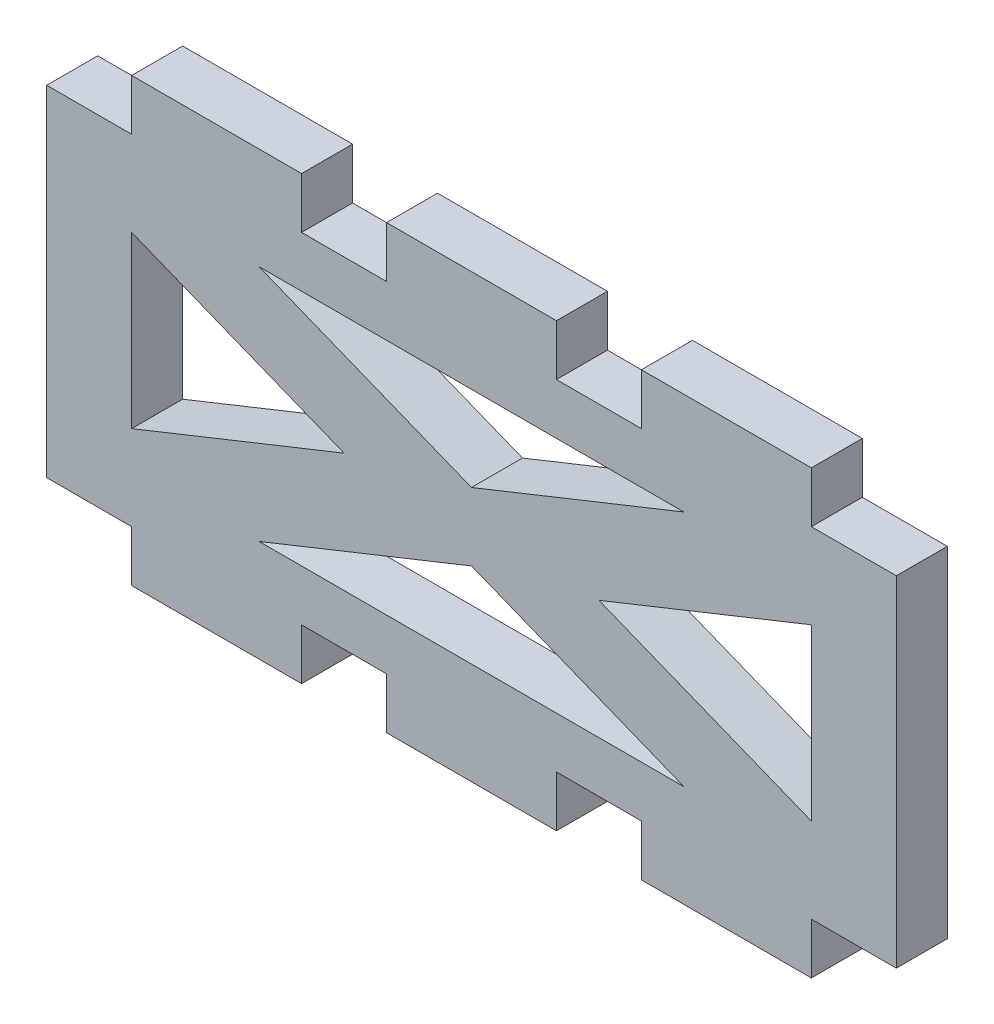
SolidWorks part; units mm, degrees
material "Thornel Mat VMA"
ref_plane "前视基准面" through (0, 0, 0) normal (0, 0, 1) x (1, 0, 0)
ref_plane "上视基准面" through (0, 0, 0) normal (0, 1, 0) x (1, 0, 0)
ref_plane "右视基准面" through (0, 0, 0) normal (1, 0, 0) x (0, 0, -1)
sketch "草图1" plane through (0, 0, 0) normal (0, 0, 1) x (1, 0, 0)
  line L0 (-25, -10) -> (-20, -10)
  line L1 (-25, -10) -> (-25, -8)
  line L2 (-25, 10) -> (-20, 10)
  line L3 (25, -10) -> (25, -8)
  line L16 (-5, 10) -> (-5, 13)
  line L17 (-20, 10) -> (-20, 13)
  line L18 (-20, 13) -> (-10, 13)
  line L19 (-10, 10) -> (-10, 13)
  line L20 (5, 10) -> (5, 13)
  line L21 (-5, 13) -> (5, 13)
  line L22 (10, 10) -> (10, 13)
  line L23 (20, 10) -> (20, 13)
  line L24 (10, 13) -> (20, 13)
  line L25 (-25, 8) -> (-25, 10)
  line L26 (-25, -2) -> (-25, 2)
  line L27 (-10, 10) -> (-5, 10)
  line L28 (5, 10) -> (10, 10)
  line L29 (20, 10) -> (25, 10)
  line L30 (25, 8) -> (25, 10)
  line L31 (25, -2) -> (25, 2)
  line L32 (20, -10) -> (20, -13)
  line L33 (10, -13) -> (20, -13)
  line L34 (10, -10) -> (10, -13)
  line L35 (5, -10) -> (5, -13)
  line L36 (-5, -13) -> (5, -13)
  line L37 (-5, -10) -> (-5, -13)
  line L38 (-10, -10) -> (-10, -13)
  line L39 (-20, -13) -> (-10, -13)
  line L40 (-20, -10) -> (-20, -13)
  line L41 (-10, -10) -> (-5, -10)
  line L42 (5, -10) -> (10, -10)
  line L43 (20, -10) -> (25, -10)
  line L44 (-25, 8) -> (-25, 2)
  line L45 (-25, -2) -> (-25, -8)
  line L46 (25, 8) -> (25, 2)
  line L47 (25, -2) -> (25, -8)
  line L48 (-25, 10) -> (25, -10) construction
  line L49 (-25, -10) -> (25, 10) construction
  line L51 (-12.5, 7) -> (12.5, 7)
  line L52 (12.5, 7) -> (0, 2)
  line L53 (-12.5, 7) -> (0, 2)
  line L55 (20, -5) -> (20, 5)
  line L56 (20, 5) -> (7.5, 0)
  line L57 (20, -5) -> (7.5, 0)
  line L58 (-12.5, -7) -> (12.5, -7)
  line L59 (12.5, -7) -> (0, -2)
  line L60 (-12.5, -7) -> (0, -2)
  line L61 (-20, -5) -> (-7.5, 0)
  line L62 (-20, 5) -> (-7.5, 0)
  line L63 (-20, -5) -> (-20, 5)
  point P0 (0, 0)
  dimension "D1" = 50
  dimension "D2" = 20
  dimension "D3" = 3
  dimension "D6" = 2
  dimension "D8" = 2
  dimension "D9" = 3
  dimension "D10" = 5
  dimension "D11" = 10
extrude "凸台-拉伸1" add sketch "草图1" along normal blind 3
